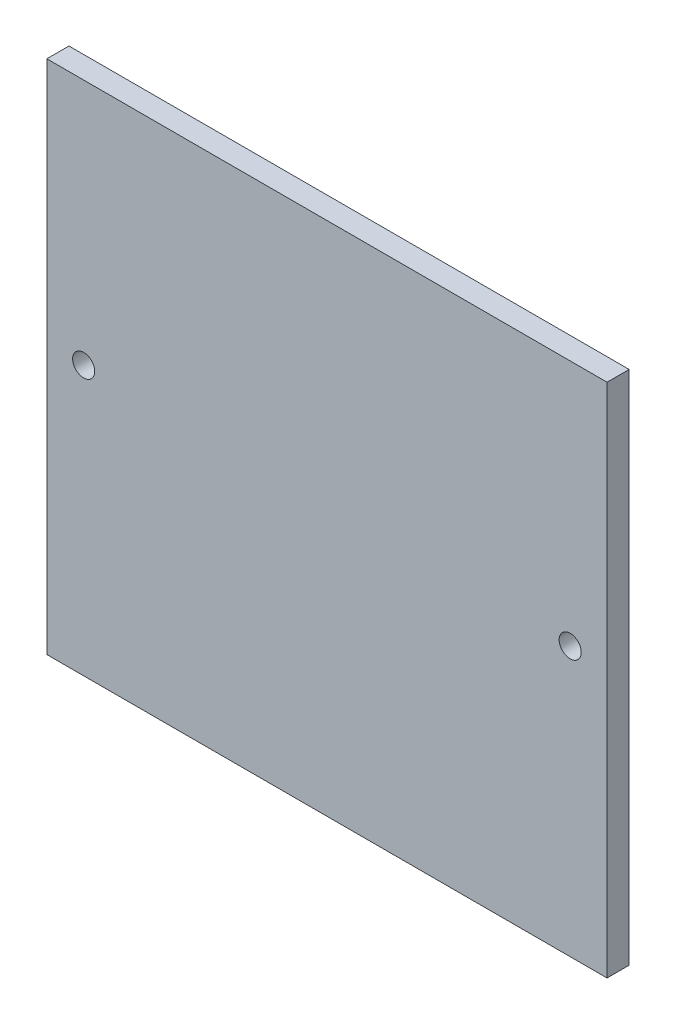
SolidWorks part; units mm, degrees
ref_plane "Plan de face" through (0, 0, 0) normal (0, 0, 1) x (1, 0, 0)
ref_plane "Plan de dessus" through (0, 0, 0) normal (0, 1, 0) x (1, 0, 0)
ref_plane "Plan de droite" through (0, 0, 0) normal (1, 0, 0) x (0, 0, -1)
sketch "Esquisse1" plane through (0, 0, 0) normal (0, 0, 1) x (1, 0, 0)
  line L1 (-31.503, 16.7246) -> (44.497, 16.7246)
  line L2 (-31.503, 16.7246) -> (-31.503, -53.2754)
  line L3 (-31.503, -53.2754) -> (44.497, -53.2754)
  line L4 (44.497, 16.7246) -> (44.497, -53.2754)
  circle A0 centre (-26.503, -16.7754) radius 1.5
  circle A1 centre (39.497, -16.7754) radius 1.5
  dimension "D3" = 3
  dimension "D4" = 3
  dimension "D1" = 76
  dimension "D2" = 70
  dimension "D5" = 5
  dimension "D6" = 5
  dimension "D7" = 33.5
  dimension "D8" = 33.5
extrude "Boss.-Extru.1" add sketch "Esquisse1" along normal blind 3
sketch "Esquisse2" plane through (0, 0, 3) normal (0, 0, 1) x (1, 0, 0)
  text T0 "<b>BGS Corp.</b>"
